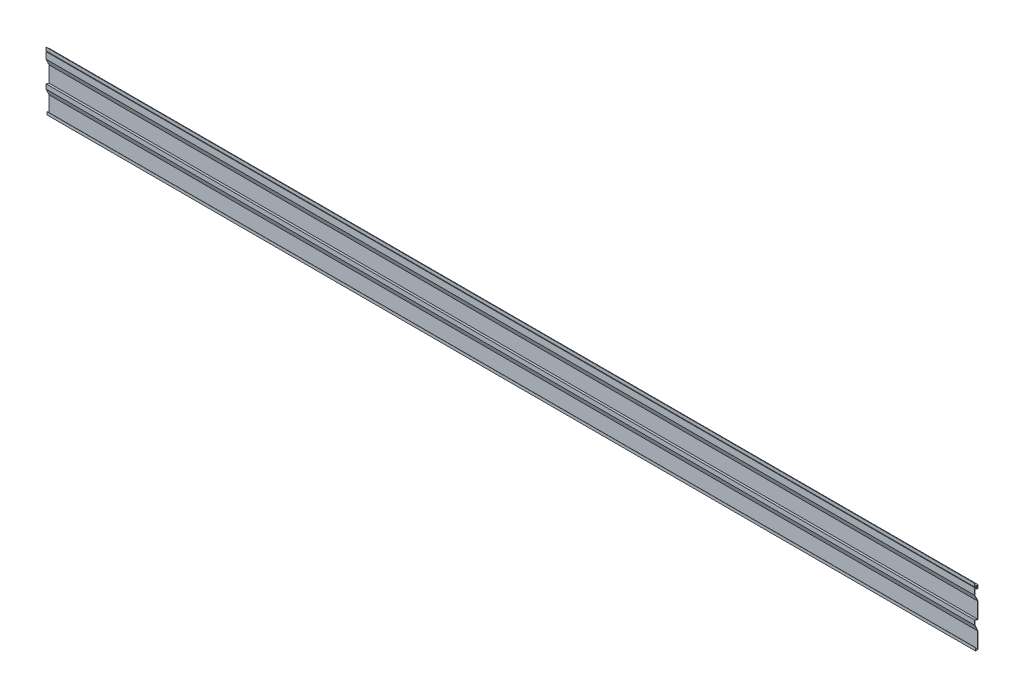
SolidWorks part; units mm, degrees
ref_plane "Спереди" through (0, 0, 0) normal (0, 0, 1) x (1, 0, 0)
ref_plane "Сверху" through (0, 0, 0) normal (0, 1, 0) x (1, 0, 0)
ref_plane "Справа" through (0, 0, 0) normal (1, 0, 0) x (0, 0, -1)
sketch "Эскиз1" plane through (0, 0, 0) normal (1, 0, 0) x (0, 0, -1)
  line L7 (-21.0405, -176.7428) -> (-11.0405, -176.7428)
  line L8 (-11.0405, -176.7428) -> (-11.0405, -112.7428)
  line L9 (-11.0405, -112.7428) -> (-23.4474, -86.7469)
  line L10 (-23.4474, -86.7469) -> (-23.4474, -71.1496)
  line L11 (-23.4474, -71.1496) -> (-11.0405, -74.6944)
  line L12 (-11.0405, -74.6944) -> (-11.0405, -10.6944)
  line L13 (-11.0405, -10.6944) -> (-23.4474, 15.3014)
  line L14 (-23.4474, 15.3014) -> (-23.4474, 40.3056)
  line L15 (-23.4474, 40.3056) -> (-17.2439, 40.3056)
  line L16 (-17.2439, 40.3056) -> (-17.2439, 32.0052)
  line L17 (-17.2439, 32.0052) -> (-11.0405, 32.0052)
  line L18 (-11.0405, 32.0052) -> (-11.0405, 45.1211)
  line L19 (-11.0405, 45.1211) -> (-23.4474, 45.1211)
  line L20 (-23.4474, 45.1211) -> (-23.4474, 56.3056)
  line L21 (-21.0405, -176.7428) -> (-21.0405, -165.4423)
  line L22 (-21.0405, -165.4423) -> (-20.3457, -165.4423)
  line L23 (-20.3457, -165.4423) -> (-20.3457, -175.264)
  line L24 (-20.3457, -175.264) -> (-12.1002, -175.264)
  line L25 (-12.1002, -175.264) -> (-12.1002, -112.7428)
  line L26 (-12.1002, -112.7428) -> (-24.5071, -86.7469)
  line L27 (-24.5071, -86.7469) -> (-24.5071, -69.0759)
  line L28 (-24.5071, -69.0759) -> (-12.1002, -72.6207)
  line L29 (-12.1002, -72.6207) -> (-12.1002, -10.6944)
  line L30 (-12.1002, -10.6944) -> (-24.5071, 15.3014)
  line L31 (-24.5071, 15.3014) -> (-24.5071, 41.2326)
  line L32 (-24.5071, 41.2326) -> (-16.2229, 41.2326)
  line L33 (-16.2229, 41.2326) -> (-16.2229, 33.3611)
  line L34 (-16.2229, 33.3611) -> (-12.1002, 33.3611)
  line L35 (-12.1002, 33.3611) -> (-12.1002, 43.8204)
  line L36 (-12.1002, 43.8204) -> (-24.5071, 43.8204)
  line L37 (-24.5071, 43.8204) -> (-24.5071, 56.3056)
  line L38 (-24.5071, 56.3056) -> (-23.4474, 56.3056)
extrude "Бобышка-Вытянуть1" add sketch "Эскиз1" along normal blind 3660
